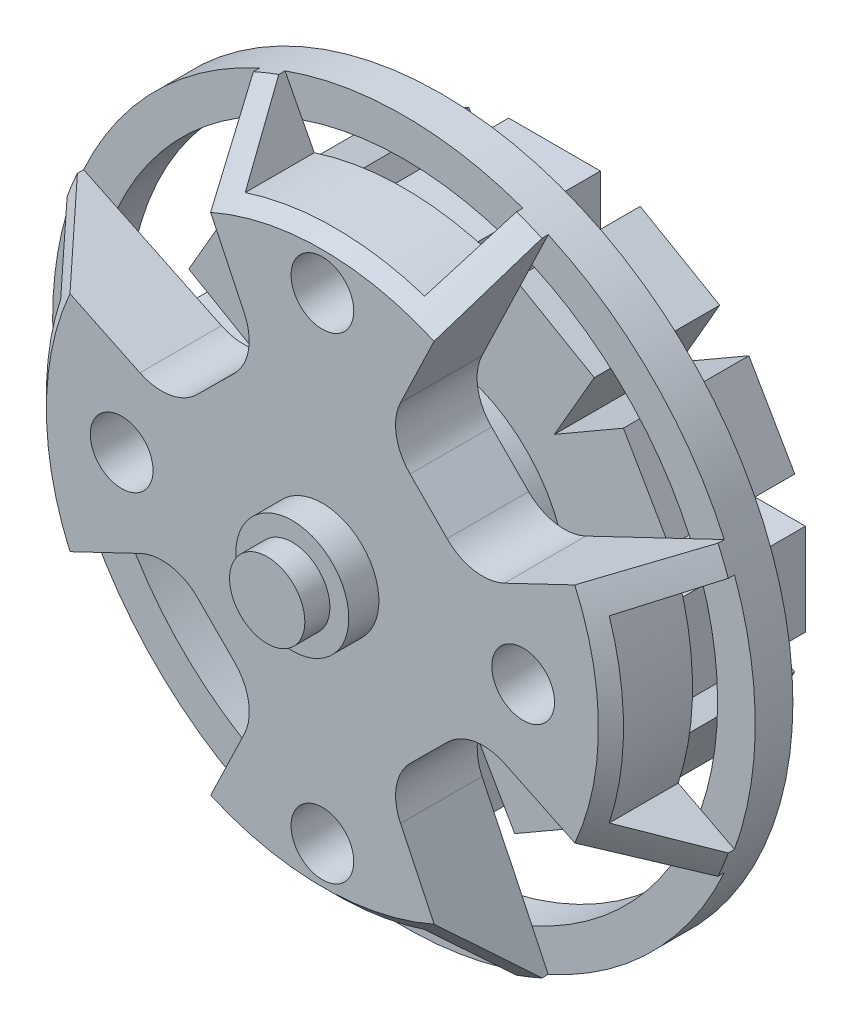
SolidWorks part; units mm, degrees
ref_plane "Спереди" through (0, 0, 0) normal (0, 0, 1) x (1, 0, 0)
ref_plane "Сверху" through (0, 0, 0) normal (0, 1, 0) x (1, 0, 0)
ref_plane "Справа" through (0, 0, 0) normal (1, 0, 0) x (0, 0, -1)
sketch "Эскиз1" plane through (0, 0, 0) normal (0, 0, 1) x (1, 0, 0)
  line L0 (0, -1000) -> (0, 49000) construction
  line L1 (-5.75, 12.7647) -> (5.75, 12.7647) construction
  line L2 (-2.5, 5.9702) -> (2.5, 5.9702) construction
  line L3 (-12.7647, 5.75) -> (-12.7647, -5.75) construction
  line L4 (-8.5214, 0) -> (0, -8.449) construction
  line L5 (-8.5214, 0) -> (0, 8.449) construction
  line L6 (0, 8.449) -> (8.5214, 0) construction
  line L7 (0, -8.449) -> (8.5214, 0) construction
  line L8 (-8.5214, 0) -> (8.5214, 0) construction
  line L9 (0, 8.449) -> (0, -8.449) construction
  line L10 (-6, 2.5) -> (-6, -2.5) construction
  line L11 (-7.2721, 3.1112) -> (-12.7647, 5.75)
  line L12 (-5.75, 12.7647) -> (-3.1134, 7.2526)
  line L13 (-4.9978, 3.4937) -> (-3.5095, 4.9694)
  line L14 (3.1112, 7.2721) -> (5.75, 12.7647)
  line L15 (12.7647, 5.75) -> (7.2526, 3.1134)
  line L16 (3.4937, 4.9978) -> (4.9694, 3.5095)
  line L17 (0, 8.5214) -> (8.449, 0) construction
  line L18 (7.2721, -3.1112) -> (12.7647, -5.75)
  line L19 (5.75, -12.7647) -> (3.1134, -7.2526)
  line L20 (4.9978, -3.4937) -> (3.5095, -4.9694)
  line L21 (8.5214, 0) -> (0, -8.449) construction
  line L22 (-3.1112, -7.2721) -> (-5.75, -12.7647)
  line L23 (-12.7647, -5.75) -> (-7.2526, -3.1134)
  line L24 (-3.4937, -4.9978) -> (-4.9694, -3.5095)
  line L25 (0, -8.5214) -> (-8.449, 0) construction
  arc A1 (-12.7647, 5.75) -> (-14, 0) centre (0, 0) ccw
  arc A2 (-5.75, 12.7647) -> (0, 14) centre (0, 0) cw
  arc A3 (-3.5095, 4.9694) -> (-3.1134, 7.2526) centre (-4.9176, 6.3896) ccw
  arc A4 (-4.9978, 3.4937) -> (-7.2721, 3.1112) centre (-6.406, 4.9139) cw
  arc A5 (5.75, 12.7647) -> (0, 14) centre (0, 0) ccw
  arc A6 (12.7647, 5.75) -> (14, 0) centre (0, 0) cw
  arc A7 (4.9694, 3.5095) -> (7.2526, 3.1134) centre (6.3896, 4.9176) ccw
  arc A8 (3.4937, 4.9978) -> (3.1112, 7.2721) centre (4.9139, 6.406) cw
  arc A9 (12.7647, -5.75) -> (14, 0) centre (0, 0) ccw
  arc A10 (5.75, -12.7647) -> (0, -14) centre (0, 0) cw
  arc A11 (3.5095, -4.9694) -> (3.1134, -7.2526) centre (4.9176, -6.3896) ccw
  arc A12 (4.9978, -3.4937) -> (7.2721, -3.1112) centre (6.406, -4.9139) cw
  arc A13 (-5.75, -12.7647) -> (0, -14) centre (0, 0) ccw
  arc A14 (-12.7647, -5.75) -> (-14, 0) centre (0, 0) cw
  arc A15 (-4.9694, -3.5095) -> (-7.2526, -3.1134) centre (-6.3896, -4.9176) ccw
  arc A16 (-3.4937, -4.9978) -> (-3.1112, -7.2721) centre (-4.9139, -6.406) cw
  point P63 (0, 0)
  dimension "D1" = 2
  dimension "D2" = 11.5
  dimension "D3" = 5
  dimension "D4" = 12
  dimension "D5" = 4
extrude "Бобышка-Вытянуть1" add sketch "Эскиз1" along normal blind 3.25
sketch "Эскиз2" plane through (0, 0, 0) normal (0, 0, -1) x (-1, 0, 0)
  circle A0 centre (0, 0) radius 14
  circle A1 centre (0, 0) radius 12.5
  arc A2 (5.75, 12.7647) -> (-5.75, 12.7647) centre (0, 0) ccw construction
  dimension "D2" = 1.5
extrude "Бобышка-Вытянуть2" add sketch "Эскиз2" along normal blind 1.5
chamfer "Фаска1" distance 3 angle 45 4 edges at (0, -14, 3.25) (-14, 0, 3.25) (0, 14, 3.25) (14, 0, 3.25)
sketch "Эскиз3" plane through (0, 0, 3.25) normal (0, 0, 1) x (1, 0, 0)
  line L0 (-5.75, 12.7647) -> (-3.1134, 7.2526) construction
  line L1 (3.1112, 7.2721) -> (5.75, 12.7647) construction
  line L2 (-4.7388, 13.1736) -> (-3.5745, 10.9304)
  line L3 (3.5745, 10.9304) -> (4.7388, 13.1736)
  line L4 (0, -1000) -> (0, 49000) construction
  line L5 (13.1736, 4.7388) -> (10.9304, 3.5745)
  line L6 (10.9304, -3.5745) -> (13.1736, -4.7388)
  line L7 (4.7388, -13.1736) -> (3.5745, -10.9304)
  line L8 (-3.5745, -10.9304) -> (-4.7388, -13.1736)
  line L9 (-13.1736, -4.7388) -> (-10.9304, -3.5745)
  line L10 (-10.9304, 3.5745) -> (-13.1736, 4.7388)
  line L11 (0, -1000) -> (0, 49000) construction
  line L12 (-1000, 0) -> (49000, 0) construction
  circle A0 centre (0, 0) radius 11.5 construction
  arc A1 (-5.75, 12.7647) -> (-12.7647, 5.75) centre (0, 0) ccw construction
  arc A2 (4.7388, 13.1736) -> (-4.7388, 13.1736) centre (0, 0) ccw
  arc A4 (-3.5745, 10.9304) -> (3.5745, 10.9304) centre (0, 0) cw
  arc A5 (12.7647, 5.75) -> (5.75, 12.7647) centre (0, 0) ccw construction
  arc A6 (13.1736, -4.7388) -> (13.1736, 4.7388) centre (0, 0) ccw
  arc A7 (10.9304, 3.5745) -> (10.9304, -3.5745) centre (0, 0) cw
  arc A8 (-4.7388, -13.1736) -> (4.7388, -13.1736) centre (0, 0) ccw
  arc A9 (3.5745, -10.9304) -> (-3.5745, -10.9304) centre (0, 0) cw
  arc A10 (-13.1736, 4.7388) -> (-13.1736, -4.7388) centre (0, 0) ccw
  arc A11 (-10.9304, -3.5745) -> (-10.9304, 3.5745) centre (0, 0) cw
  circle A12 centre (-8, 0) radius 1.25
  circle A13 centre (8, 0) radius 1.25
  circle A14 centre (0, 9.5) radius 1.25
  circle A15 centre (0, -9.5) radius 1.25
  point P39 (0, 0)
  dimension "D1" = 2.5
  dimension "D3" = 2.5
  dimension "D4" = 16
  dimension "D5" = 19
  dimension "D2" = 4
extrude "Вырез-Вытянуть2" cut sketch "Эскиз3" against normal up to surface (3.25 mm away) up to face at (0, 0, 0)
sketch "Эскиз4" plane through (0, 0, 3.25) normal (0, 0, 1) x (1, 0, 0)
  circle A0 centre (0, 0) radius 2.25
  dimension "D1" = 4.5
extrude "Бобышка-Вытянуть3" add sketch "Эскиз4" along normal blind 1.2
sketch "Эскиз6" plane through (0, 0, 4.45) normal (0, 0, 1) x (1, 0, 0)
  circle A0 centre (0, 0) radius 1.5
  dimension "D1" = 3
extrude "Бобышка-Вытянуть4" add sketch "Эскиз6" along normal blind 1
sketch "Эскиз7" plane through (0, 0, 0) normal (0, 0, -1) x (-1, 0, 0)
  circle A0 centre (0, 0) radius 5.5
  dimension "D1" = 11
extrude "Бобышка-Вытянуть5" add sketch "Эскиз7" along normal blind 1
sketch "Эскиз8" plane through (0, 0, -1) normal (0, 0, -1) x (-1, 0, 0)
  line L0 (0, -1000) -> (0, 49000) construction
  line L1 (-1000, 0) -> (49000, 0) construction
  line L2 (-1008.4801, 12.5) -> (48991.5199, 12.5) construction
  line L3 (-1.8286, 10) -> (1.8286, 10)
  line L4 (-1.8286, 10) -> (-1.8286, 6.8246)
  line L5 (-0.911, 3.4) -> (0.911, 3.4)
  line L6 (1.8286, 10) -> (1.8286, 6.8246)
  line L7 (-1.8286, 10) -> (1.8286, 3) construction
  line L8 (-1.8286, 3) -> (1.8286, 10) construction
  line L9 (3.4164, 9.5746) -> (6.5836, 7.7459)
  line L10 (3.4164, 9.5746) -> (1.8286, 6.8246)
  line L11 (0.911, 3.4) -> (2.489, 2.489)
  line L12 (6.5836, 7.7459) -> (4.9959, 4.9959)
  line L13 (3.4164, 9.5746) -> (3.0836, 1.6838) construction
  line L14 (-0.0836, 3.5124) -> (6.5836, 7.7459) construction
  line L15 (7.7459, 6.5836) -> (9.5746, 3.4164)
  line L16 (7.7459, 6.5836) -> (4.9959, 4.9959)
  line L17 (2.489, 2.489) -> (3.4, 0.911)
  line L18 (9.5746, 3.4164) -> (6.8246, 1.8286)
  line L19 (7.7459, 6.5836) -> (3.5124, -0.0836) construction
  line L20 (1.6838, 3.0836) -> (9.5746, 3.4164) construction
  line L21 (10, 1.8286) -> (10, -1.8286)
  line L22 (10, 1.8286) -> (6.8246, 1.8286)
  line L23 (3.4, 0.911) -> (3.4, -0.911)
  line L24 (10, -1.8286) -> (6.8246, -1.8286)
  line L25 (10, 1.8286) -> (3, -1.8286) construction
  line L26 (3, 1.8286) -> (10, -1.8286) construction
  line L27 (9.5746, -3.4164) -> (7.7459, -6.5836)
  line L28 (9.5746, -3.4164) -> (6.8246, -1.8286)
  line L29 (3.4, -0.911) -> (2.489, -2.489)
  line L30 (7.7459, -6.5836) -> (4.9959, -4.9959)
  line L31 (9.5746, -3.4164) -> (1.6838, -3.0836) construction
  line L32 (3.5124, 0.0836) -> (7.7459, -6.5836) construction
  line L33 (6.5836, -7.7459) -> (3.4164, -9.5746)
  line L34 (6.5836, -7.7459) -> (4.9959, -4.9959)
  line L35 (2.489, -2.489) -> (0.911, -3.4)
  line L36 (3.4164, -9.5746) -> (1.8286, -6.8246)
  line L37 (6.5836, -7.7459) -> (-0.0836, -3.5124) construction
  line L38 (3.0836, -1.6838) -> (3.4164, -9.5746) construction
  line L39 (1.8286, -10) -> (-1.8286, -10)
  line L40 (1.8286, -10) -> (1.8286, -6.8246)
  line L41 (0.911, -3.4) -> (-0.911, -3.4)
  line L42 (-1.8286, -10) -> (-1.8286, -6.8246)
  line L43 (1.8286, -10) -> (-1.8286, -3) construction
  line L44 (1.8286, -3) -> (-1.8286, -10) construction
  line L45 (-3.4164, -9.5746) -> (-6.5836, -7.7459)
  line L46 (-3.4164, -9.5746) -> (-1.8286, -6.8246)
  line L47 (-0.911, -3.4) -> (-2.489, -2.489)
  line L48 (-6.5836, -7.7459) -> (-4.9959, -4.9959)
  line L49 (-3.4164, -9.5746) -> (-3.0836, -1.6838) construction
  line L50 (0.0836, -3.5124) -> (-6.5836, -7.7459) construction
  line L51 (-7.7459, -6.5836) -> (-9.5746, -3.4164)
  line L52 (-7.7459, -6.5836) -> (-4.9959, -4.9959)
  line L53 (-2.489, -2.489) -> (-3.4, -0.911)
  line L54 (-9.5746, -3.4164) -> (-6.8246, -1.8286)
  line L55 (-7.7459, -6.5836) -> (-3.5124, 0.0836) construction
  line L56 (-1.6838, -3.0836) -> (-9.5746, -3.4164) construction
  line L57 (-10, -1.8286) -> (-10, 1.8286)
  line L58 (-10, -1.8286) -> (-6.8246, -1.8286)
  line L59 (-3.4, -0.911) -> (-3.4, 0.911)
  line L60 (-10, 1.8286) -> (-6.8246, 1.8286)
  line L61 (-10, -1.8286) -> (-3, 1.8286) construction
  line L62 (-3, -1.8286) -> (-10, 1.8286) construction
  line L63 (-9.5746, 3.4164) -> (-7.7459, 6.5836)
  line L64 (-9.5746, 3.4164) -> (-6.8246, 1.8286)
  line L65 (-3.4, 0.911) -> (-2.489, 2.489)
  line L66 (-7.7459, 6.5836) -> (-4.9959, 4.9959)
  line L67 (-9.5746, 3.4164) -> (-1.6838, 3.0836) construction
  line L68 (-3.5124, -0.0836) -> (-7.7459, 6.5836) construction
  line L69 (-6.5836, 7.7459) -> (-3.4164, 9.5746)
  line L70 (-6.5836, 7.7459) -> (-4.9959, 4.9959)
  line L71 (-2.489, 2.489) -> (-0.911, 3.4)
  line L72 (-3.4164, 9.5746) -> (-1.8286, 6.8246)
  line L73 (-6.5836, 7.7459) -> (0.0836, 3.5124) construction
  line L74 (-3.0836, 1.6838) -> (-3.4164, 9.5746) construction
  circle A1 centre (0, 0) radius 12.5 construction
  point P9 (0, 6.5)
  point P21 (3.25, 5.6292)
  point P26 (5.6292, 3.25)
  point P31 (6.5, 0)
  point P36 (5.6292, -3.25)
  point P41 (3.25, -5.6292)
  point P46 (0, -6.5)
  point P51 (-3.25, -5.6292)
  point P56 (-5.6292, -3.25)
  point P61 (-6.5, 0)
  point P66 (-5.6292, 3.25)
  point P71 (-3.25, 5.6292)
  point P72 (0, 0)
  dimension "D1" = 2.5
  dimension "D2" = 7
  dimension "D3" = 12
extrude "Бобышка-Вытянуть6" add sketch "Эскиз8" along normal blind 5
equation "\"2ю5\"=2.3"
